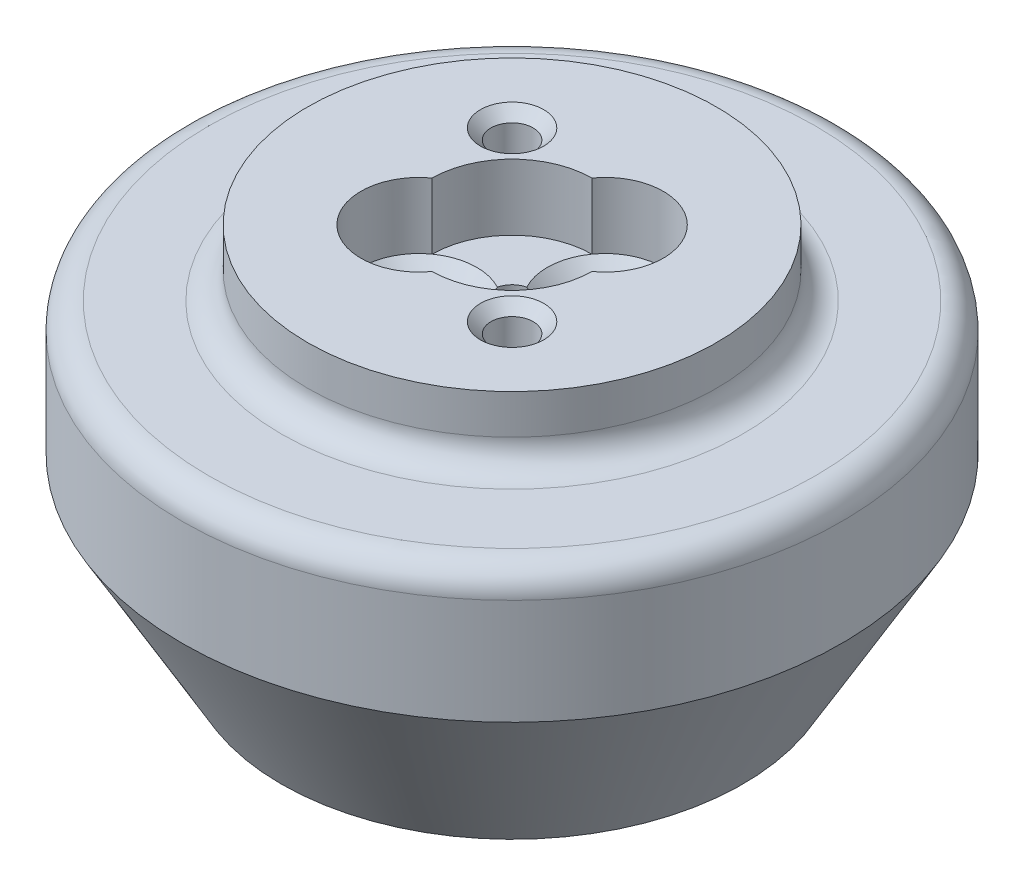
SolidWorks part; units mm, degrees
material "Brass"
ref_plane "Front" through (0, 0, 0) normal (0, 0, 1) x (1, 0, 0)
ref_plane "Top" through (0, 0, 0) normal (0, 1, 0) x (1, 0, 0)
ref_plane "Right" through (0, 0, 0) normal (1, 0, 0) x (0, 0, -1)
sketch "Sketch1" plane through (0, 0, 0) normal (0, 1, 0) x (1, 0, 0)
  circle A0 centre (0, 0) radius 7.1438
  circle A1 centre (0, 0) radius 12.5
  dimension "D1" = 14.2875
  dimension "D2" = 25
extrude "Boss-Extrude1" add sketch "Sketch1" along normal blind 10
sketch "Sketch2" plane through (0, 10, 0) normal (0, 1, 0) x (1, 0, 0)
  circle A0 centre (0, 0) radius 12.5 construction
  circle A1 centre (0, 0) radius 12.5
extrude "Boss-Extrude2" add sketch "Sketch2" along normal blind 1.5
chamfer "Chamfer1" distance 3.75 angle 60 1 edges at (0, 0, 12.5)
sketch "Sketch8" plane through (0, 11.5, 0) normal (0, 1, 0) x (1, 0, 0)
  circle A1 centre (0, 0) radius 7.75
  circle A2 centre (0, 0) radius 3.05
  dimension "D1" = 6.1
  dimension "D2" = 15.5
extrude "Boss-Extrude3" add sketch "Sketch8" along normal blind 2.5
sketch "Sketch9" plane through (0, 11.5, 0) normal (0, 1, 0) x (1, 0, 0)
  circle A0 centre (1.7678, 1.7678) radius 0.7 construction
  circle A2 centre (-1.7678, -1.7678) radius 0.7 construction
  circle A4 centre (1.7678, 1.7678) radius 0.7 construction
  circle A6 centre (-1.7678, -1.7678) radius 0.7 construction
hole_wizard "CSK for M2 Flat Head Machine Screw1" positions "3DSketch2" profile "Sketch11" countersink size "M2" standard "ANSI Metric"
sketch3d "3DSketch2"
  point P0 (-1.7678, 11.5, 1.7678)
  point P6 (1.7678, 11.5, -1.7678)
sketch "Sketch11" plane through (-1.7678, 11.5, 1.7678) normal (1, 0, 0) x (0, 0, 1)
  line L0 (0, 0) -> (0, 11.5)
  line L1 (0, 11.5) -> (1.2, 11.5)
  line L2 (1.2, 11.5) -> (1.2, 1)
  line L3 (1.2, 1) -> (2.2, 0)
  line L5 (2.2, 0) -> (0, 0)
  line L6 (-1.2, 1) -> (-2.2, 0) construction
  line L11 (0, -6.35) -> (0, 107.95) construction
  dimension "Thru Hole Dia." = 2.4
  dimension "Thru Hole Depth" = 11.5
  dimension "Near C'Sink Dia." = 4.4
  dimension "Near C'Sink Angle" = 90
sketch "Sketch16" plane through (0, 11.5, 0) normal (0, 1, 0) x (1, 0, 0)
  circle A0 centre (0, 0) radius 0.75
  dimension "D1" = 1.5
extrude "Cut-Extrude1" cut sketch "Sketch16" against normal through all
sketch "Sketch17" plane through (0, 14, 0) normal (0, 1, 0) x (1, 0, 0)
  circle A0 centre (3.182, -3.182) radius 0.7 construction
  circle A1 centre (-3.182, 3.182) radius 0.7 construction
  circle A2 centre (3.182, -3.182) radius 0.7
  circle A3 centre (-3.182, 3.182) radius 0.7
hole_wizard "M2x0.4 Tapped Hole1" positions "3DSketch4" profile "Sketch19" tap size "M2x0.4" standard "ANSI Metric" end condition through all
sketch3d "3DSketch4"
  point P0 (3.182, 14, 3.182)
  point P3 (-3.182, 14, -3.182)
sketch "Sketch19" plane through (3.182, 14, 3.182) normal (1, 0, 0) x (0, 0, 1)
  line L0 (0, 0) -> (0, 14)
  line L1 (0, 14) -> (0.8, 14)
  line L2 (0.8, 14) -> (0.8, 0.4)
  line L3 (0.8, 0.4) -> (1.2, 0)
  line L5 (1.2, 0) -> (0, 0)
  line L6 (-0.8, 0.4) -> (-1.2, 0) construction
  line L11 (0, -6.35) -> (0, 107.95) construction
  dimension "Thru Tap Drill Dia." = 1.6
  dimension "Thru Tap Drill Depth" = 14
  dimension "Near C'Sink Dia." = 2.4
  dimension "Near C'Sink Angle" = 90
cosmetic thread "Hole Thread3" parameters "D2"=2
cosmetic thread "Hole Thread4" parameters "D2"=2
sketch "Sketch20" plane through (0, 14, 0) normal (0, 1, 0) x (1, 0, 0)
  arc A4 (0.02, -3.0499) -> (0.1721, -0.73) centre (-1.7678, -1.7678) ccw
  arc A5 (-0.73, 0.1721) -> (0.1721, -0.73) centre (0, 0) ccw
  arc A6 (-0.73, 0.1721) -> (-3.0499, 0.02) centre (-1.7678, -1.7678) ccw
  arc A7 (-3.0499, 0.02) -> (0.02, -3.0499) centre (-1.7678, -1.7678) ccw
  arc A8 (0.02, -3.0499) -> (0.1721, -0.73) centre (-1.7678, -1.7678) ccw
  arc A9 (-0.73, 0.1721) -> (0.1721, -0.73) centre (0, 0) ccw
  arc A10 (-0.73, 0.1721) -> (-3.0499, 0.02) centre (-1.7678, -1.7678) ccw
  arc A11 (-3.0499, 0.02) -> (0.02, -3.0499) centre (-1.7678, -1.7678) ccw
  arc A12 (-0.02, 3.0499) -> (-0.1721, 0.73) centre (1.7678, 1.7678) ccw
  arc A13 (0.73, -0.1721) -> (-0.1721, 0.73) centre (0, 0) ccw
  arc A14 (0.73, -0.1721) -> (3.0499, -0.02) centre (1.7678, 1.7678) ccw
  arc A15 (3.0499, -0.02) -> (-0.02, 3.0499) centre (1.7678, 1.7678) ccw
  arc A16 (-0.02, 3.0499) -> (-0.1721, 0.73) centre (1.7678, 1.7678) ccw
  arc A17 (0.73, -0.1721) -> (-0.1721, 0.73) centre (0, 0) ccw
  arc A18 (0.73, -0.1721) -> (3.0499, -0.02) centre (1.7678, 1.7678) ccw
  arc A19 (3.0499, -0.02) -> (-0.02, 3.0499) centre (1.7678, 1.7678) ccw
  dimension "D1" = 0
  dimension "D2" = 0
extrude "Cut-Extrude2" cut sketch "Sketch20" against normal up to vertex (2.5 mm away)
fillet "Fillet1" radius 1 2 edges at (0, 11.5, 7.75) (0, 11.5, 12.5)
